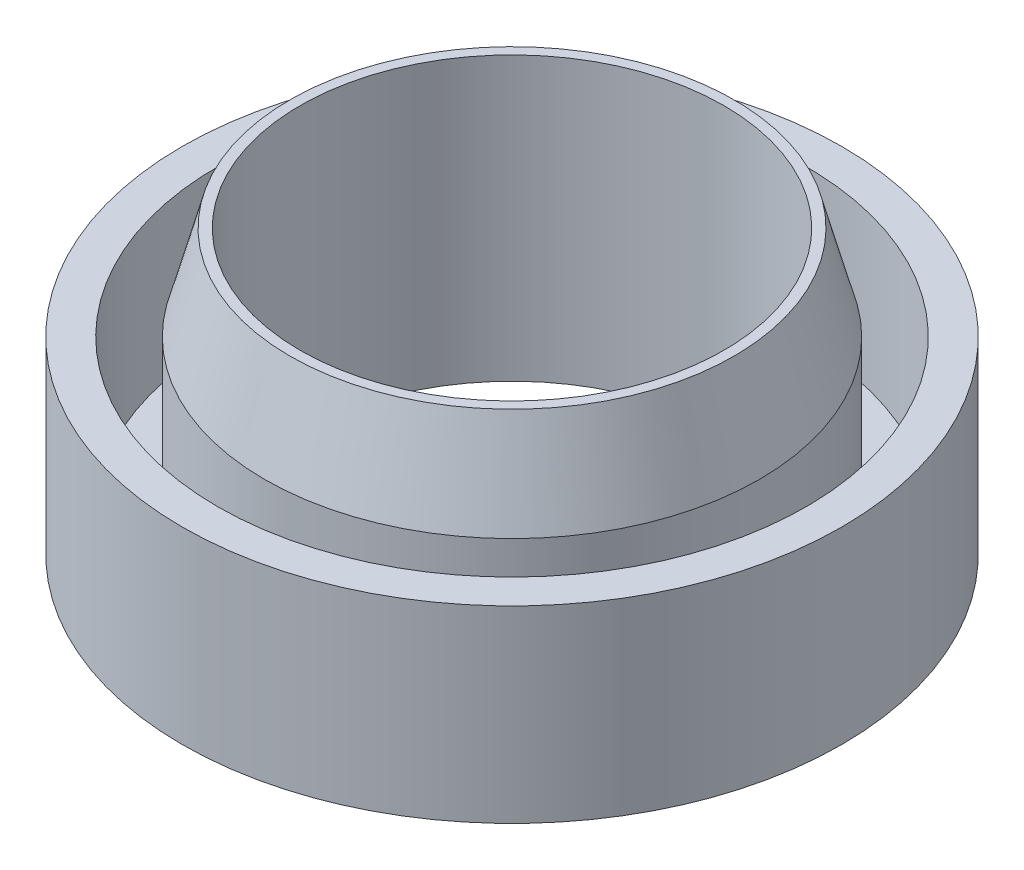
SolidWorks part; units mm, degrees
ref_plane "Front Plane" through (0, 0, 0) normal (0, 0, 1) x (1, 0, 0)
ref_plane "Top Plane" through (0, 0, 0) normal (0, 1, 0) x (1, 0, 0)
ref_plane "Right Plane" through (0, 0, 0) normal (1, 0, 0) x (0, 0, -1)
sketch "Sketch1" plane through (0, 0, 0) normal (0, 1, 0) x (1, 0, 0)
  circle A0 centre (0, 0) radius 14
  dimension "D1" = 28
extrude "Boss-Extrude1" add sketch "Sketch1" along normal blind 12
sketch "Sketch2" plane through (0, 12, 0) normal (0, 1, 0) x (1, 0, 0)
  circle A0 centre (0, 0) radius 9
  dimension "D1" = 18
extrude "Cut-Extrude1" cut sketch "Sketch2" against normal up to next
sketch "Sketch3" plane through (0, 12, 0) normal (0, 1, 0) x (1, 0, 0)
  circle A0 centre (0, 0) radius 10.5
  circle A1 centre (0, 0) radius 12.5
  dimension "D1" = 25
  dimension "D2" = 21
extrude "Cut-Extrude2" cut sketch "Sketch3" against normal blind 10.5
sketch "Sketch4" plane through (0, 12, 0) normal (0, 1, 0) x (1, 0, 0)
  circle A1 centre (0, 0) radius 12.5 construction
  circle A2 centre (0, 0) radius 14
  circle A3 centre (0, 0) radius 14
  circle A4 centre (0, 0) radius 12.5
  dimension "D1" = 0
extrude "Cut-Extrude3" cut sketch "Sketch4" against normal blind 4
chamfer "Chamfer1" distance 4 angle 15 1 edges at (0, 12, 10.5)
